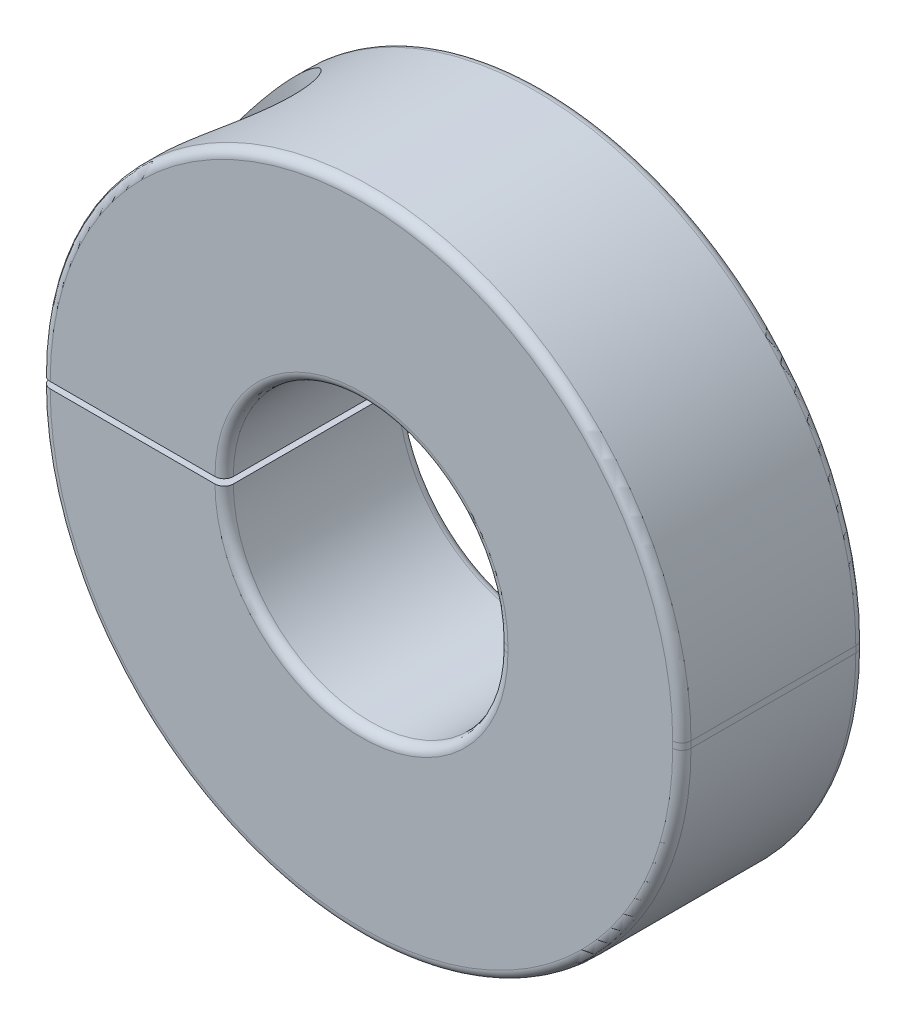
SolidWorks part; units mm, degrees
ref_plane "Front Plane" through (0, 0, 0) normal (0, 0, 1) x (1, 0, 0)
ref_plane "Top Plane" through (0, 0, 0) normal (0, 1, 0) x (1, 0, 0)
ref_plane "Right Plane" through (0, 0, 0) normal (1, 0, 0) x (0, 0, -1)
sketch "Sketch1" plane through (0, 0, 0) normal (0, 0, 1) x (1, 0, 0)
  line L0 (-22.225, 0) -> (-9.525, 0) construction
  line L1 (-22.225, 0.2223) -> (-9.525, 0.2223)
  line L2 (-22.225, -0.2223) -> (-9.525, -0.2223)
  line L3 (9.525, 0.2223) -> (22.225, 0.2223) construction
  line L4 (9.525, -0.2223) -> (22.225, -0.2223) construction
  line L5 (0, 0) -> (0, 22.225) construction
  line L6 (22.225, 0.2223) -> (22.225, -0.2223)
  line L7 (9.525, 0.2223) -> (9.525, -0.2223)
  circle A0 centre (0, 0) radius 22.225 construction
  circle A1 centre (0, 0) radius 9.525 construction
  arc A2 (-22.225, 0.2223) -> (22.225, 0.2223) centre (0, 0.2223) cw
  arc A3 (-22.225, -0.2223) -> (22.225, -0.2223) centre (0, -0.2223) ccw
  arc A4 (-9.525, 0.2223) -> (9.525, 0.2223) centre (0, 0.2223) cw
  arc A5 (-9.525, -0.2223) -> (9.525, -0.2223) centre (0, -0.2223) ccw
  point P4 (22.225, 0)
  dimension "Bore Dia" = 19.05
  dimension "OD" = 44.45
  dimension "Separation" = 0.4445
extrude "Extrude1" add sketch "Sketch1" along normal mid plane 12.7
sketch "Sketch4" plane through (0, 0, 0) normal (0, 0, 1) x (1, 0, 0)
  line L0 (-15.875, 22.4473) -> (-11.1125, 22.4473)
  line L1 (-11.1125, 22.4473) -> (-11.1125, 3.3973)
  line L2 (-11.1125, 3.3973) -> (-12.7, 3.3972)
  line L3 (-12.7, 3.3972) -> (-12.7, -22.4473)
  line L4 (-12.7, -22.4473) -> (-15.875, -22.4473)
  line L5 (-15.875, -22.4473) -> (-15.875, 22.4473)
  line L6 (-11.1125, 9.7472) -> (-20.6375, 9.7472) construction
  line L7 (-15.875, 22.4473) -> (-15.875, 24.9873) construction
  line L8 (-11.1125, 22.4473) -> (0, 22.4473) construction
  line L9 (0, -22.4473) -> (-12.7, -22.4473) construction
  line L10 (-22.225, 0) -> (-9.525, 0) construction
  line L11 (-22.225, 0.2223) -> (-9.525, 0.2223) construction
  circle A0 centre (0, 0) radius 22.225 construction
  arc A1 (22.225, 0.2223) -> (-22.225, 0.2223) centre (0, 0.2223) ccw construction
  circle A2 centre (0, 0) radius 9.525 construction
  arc A3 (-22.225, -0.2222) -> (22.225, -0.2223) centre (0, -0.2223) ccw construction
  point P13 (-15.875, 0)
  point P19 (-15.875, 0)
  point P20 (-15.875, 9.7472)
  dimension "D1" = 6.35
  dimension "D2" = 12.7
  dimension "D3" = 3.175
  dimension "D4" = 9.525
  dimension "D5" = 2.54
  dimension "Screw Dia" = 6.35
revolve "Cut-Revolve1" cut sketch "Sketch4" angle 360 about L5
sketch "Sketch6" plane through (0, 0, 0) normal (0, 0, 1) x (1, 0, 0)
  line L0 (-15.875, 9.7472) -> (-11.1125, 9.7472)
  line L1 (-11.1125, 9.7472) -> (-20.6375, 9.7472) construction
  line L2 (-11.1125, 9.7472) -> (-11.1125, 3.3973)
  line L3 (-11.1125, 3.3973) -> (-12.7, 3.3972)
  line L4 (-12.7, 3.3972) -> (-12.7, -9.3027)
  line L5 (-12.7, 3.3972) -> (-12.7, -22.4473) construction
  line L6 (-12.7, -9.3027) -> (-15.875, -9.3027)
  line L7 (-15.875, -22.4473) -> (-15.875, 22.4473) construction
  line L8 (-15.875, -9.3027) -> (-15.875, 9.7472)
  line L9 (-12.7, -9.3027) -> (-19.05, -9.3027) construction
  dimension "Head Ht" = 6.35
  dimension "Screw Lg" = 19.05
revolve "Revolve1" add sketch "Sketch6" angle 360 about L8
sketch "Sketch7" plane through (0, 9.7472, 0) normal (0, 1, 0) x (-1, 0, 0)
  line L1 (15.875, -2.9329) -> (18.415, -1.4665)
  line L2 (18.415, -1.4665) -> (18.415, 1.4665)
  line L3 (18.415, 1.4665) -> (15.875, 2.9329)
  line L4 (15.875, 2.9329) -> (13.335, 1.4665)
  line L5 (13.335, 1.4665) -> (13.335, -1.4665)
  line L6 (13.335, -1.4665) -> (15.875, -2.9329)
  circle A0 centre (15.875, 0) radius 2.54 construction
  dimension "D1" = 5.08
extrude "Cut-Extrude2" cut sketch "Sketch7" against normal blind 3.175
fillet "Fillet1" radius 0.635 12 edges at (0, 9.7472, -6.35) (0, 9.7472, 6.35) (0, 22.4473, -6.35) (0, 22.4473, 6.35) (0, -22.4473, -6.35) (0, -22.4473, 6.35) (22.225, 0, -6.35) (22.225, 0, 6.35) (0, -9.7472, -6.35) (9.525, 0, -6.35) (0, -9.7472, 6.35) (9.525, 0, 6.35)
chamfer "Chamfer2" distance 0.254 angle 45 1 edges at (-15.875, 9.7472, -4.7625)
equation "\"D1@Sketch4\" = \"Screw Dia@Sketch4\""
equation "\"D4@Sketch4\" = \"Screw Dia@Sketch4\"*1.5"
equation "\"D1@Sketch7\" = \"Screw Dia@Sketch4\"*.8"
equation "\"D1@Cut-Extrude2\" = \"Head Ht@Sketch6\"/2"
equation "\"D3@Sketch4\" = \"D1@Sketch4\"*.5"
equation "\"D1@Fillet1\" = \"Width@Extrude1\"*.05"
equation "\"Screw Lg@Sketch6\" = \"Head Ht@Sketch6\"*3"
equation "\"Separation@Sketch1\" = \"OD@Sketch1\"*.01"
